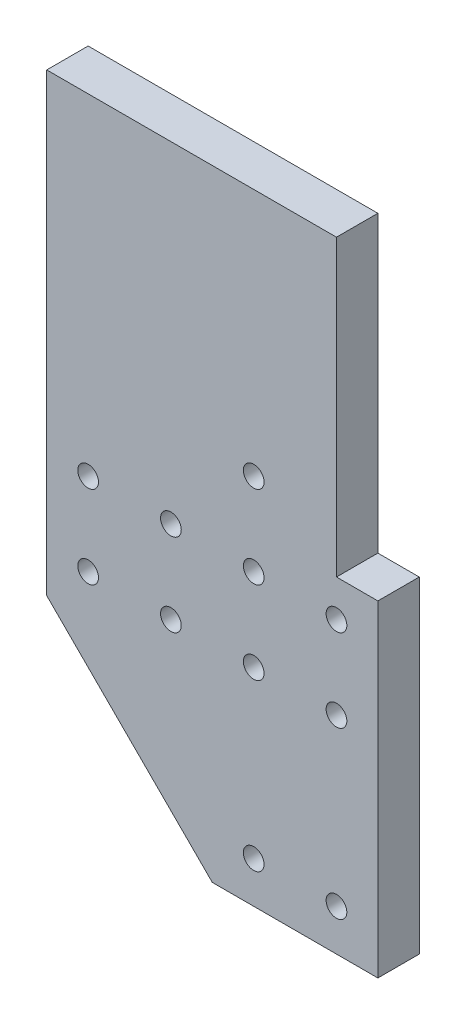
SolidWorks part; units mm, degrees
ref_plane "Front Plane" through (0, 0, 0) normal (0, 0, 1) x (1, 0, 0)
ref_plane "Top Plane" through (0, 0, 0) normal (0, 1, 0) x (1, 0, 0)
ref_plane "Right Plane" through (0, 0, 0) normal (1, 0, 0) x (0, 0, -1)
sketch "Sketch1" plane through (0, 0, 0) normal (0, 0, 1) x (1, 0, 0)
  line L0 (0, 0) -> (40, 0)
  line L4 (-40, 80) -> (-40, 40)
  line L5 (-40, 40) -> (0, 0)
  line L7 (-40, 150) -> (-40, 80)
  line L8 (-40, 150) -> (30, 150)
  line L9 (30, 150) -> (30, 78.8988)
  line L10 (30, 78.8988) -> (40, 78.8988)
  line L11 (40, 78.8988) -> (40, 0)
  dimension "D1" = 40
  dimension "D2" = 40
  dimension "D3" = 40
  dimension "D4" = 40
  dimension "D5" = 150
  dimension "D6" = 10
  dimension "D7" = 78.8988
extrude "Boss-Extrude1" add sketch "Sketch1" along normal blind 10
sketch "Sketch2" plane through (0, 0, 10) normal (0, 0, 1) x (1, 0, 0)
  line L0 (0, 0) -> (40, 0) construction
  line L1 (40, 0) -> (40, 78.8988) construction
  line L2 (-40, 150) -> (-40, 40) construction
  circle A0 centre (-30, 70) radius 2.5
  circle A1 centre (-10, 70) radius 2.5
  circle A2 centre (-30, 50) radius 2.5
  circle A3 centre (-10, 50) radius 2.5
  circle A4 centre (10, 50) radius 2.5
  circle A5 centre (30, 50) radius 2.5
  circle A6 centre (10, 10) radius 2.5
  circle A7 centre (30, 10) radius 2.5
  circle A8 centre (10, 90) radius 2.5
  circle A10 centre (10, 70) radius 2.5
  circle A11 centre (30, 70) radius 2.5
  point P18 (10, 88.9928)
  point P24 (0, 0)
  point P25 (0, 0)
  point P26 (0, 0)
  point P27 (0, 0)
  point P28 (0, 0)
  point P29 (0, 0)
  point P30 (0, 0)
  point P31 (0, 0)
  point P32 (0, 0)
  point P33 (0, 0)
  point P34 (0, 0)
  dimension "D12" = 20
  dimension "D4" = 5
  dimension "D2" = 10
  dimension "D3" = 20
  dimension "D5" = 40
  dimension "D6" = 10
  dimension "D7" = 20
  dimension "D8" = 50
  dimension "D9" = 20
  dimension "D10" = 20
  dimension "D11" = 10
extrude "Cut-Extrude1" cut sketch "Sketch2" against normal up to next
